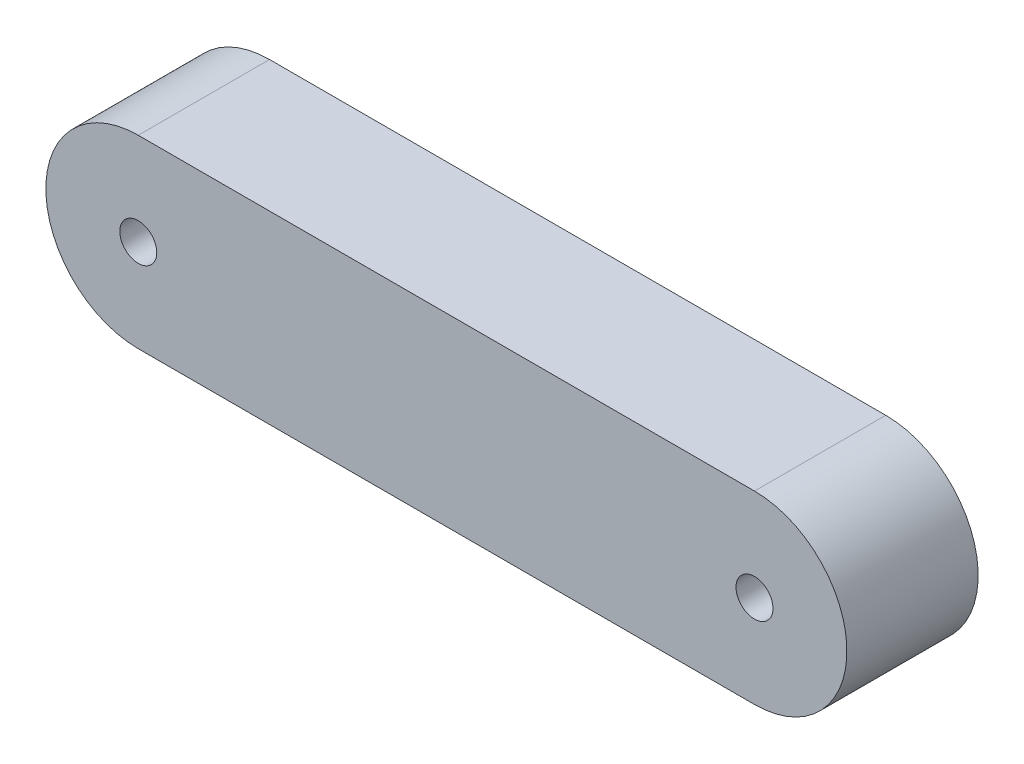
SolidWorks part; units mm, degrees
ref_plane "Front Plane" through (0, 0, 0) normal (0, 0, 1) x (1, 0, 0)
ref_plane "Top Plane" through (0, 0, 0) normal (0, 1, 0) x (1, 0, 0)
ref_plane "Right Plane" through (0, 0, 0) normal (1, 0, 0) x (0, 0, -1)
sketch "Sketch1" plane through (0, 0, 0) normal (0, 0, 1) x (1, 0, 0)
  line L0 (-100, 0) -> (100, 0) construction
  line L1 (-100, 30) -> (100, 30)
  line L2 (-100, -30) -> (100, -30)
  arc A0 (-100, 30) -> (-100, -30) centre (-100, 0) ccw
  arc A1 (100, -30) -> (100, 30) centre (100, 0) ccw
  circle A2 centre (-100, 0) radius 6
  circle A3 centre (100, 0) radius 6
  point P3 (0, 0)
  dimension "D1" = 30
  dimension "D3" = 12
  dimension "D2" = 200
extrude "Boss-Extrude1" add sketch "Sketch1" along normal blind 42.6
